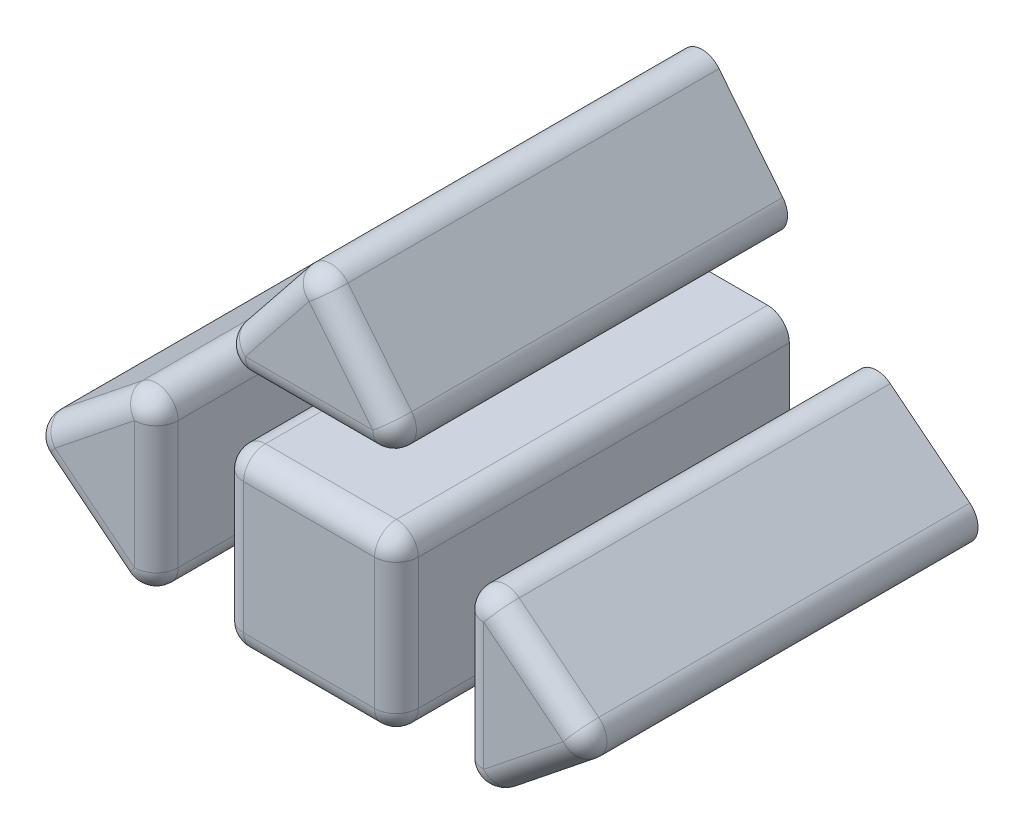
SolidWorks part; units mm, degrees
material "ABS"
ref_plane "Front Plane" through (0, 0, 0) normal (0, 0, 1) x (1, 0, 0)
ref_plane "Top Plane" through (0, 0, 0) normal (0, 1, 0) x (1, 0, 0)
ref_plane "Right Plane" through (0, 0, 0) normal (1, 0, 0) x (0, 0, -1)
sketch "Sketch1" plane through (0, 0, 0) normal (0, 0, 1) x (1, 0, 0)
  line L0 (0, -15) -> (0, 15) construction
  line L1 (-15, 0) -> (15, 0) construction
  line L2 (-0.7806, 12.27) -> (-3.699, 8.625)
  line L3 (-2.9183, 7) -> (2.9183, 7)
  line L4 (3.699, 8.625) -> (0.7806, 12.27)
  line L5 (8.625, -3.699) -> (12.27, -0.7806)
  line L6 (12.27, 0.7806) -> (8.625, 3.699)
  line L7 (7, 2.9183) -> (7, -2.9183)
  line L9 (-3, -4) -> (3, -4)
  line L10 (-4, -3) -> (-4, 3)
  line L11 (-8.625, 3.699) -> (-12.27, 0.7806)
  line L12 (-12.27, -0.7806) -> (-8.625, -3.699)
  line L13 (-7, -2.9183) -> (-7, 2.9183)
  line L14 (-3, 4) -> (3, 4)
  line L15 (4, -3) -> (4, 3)
  line L16 (-4, -4) -> (4, 4) construction
  line L20 (-4, 4) -> (4, -4) construction
  line L21 (0, -13.245) -> (5, -7) [skipped]
  line L22 (5, -7) -> (-5, -7) [skipped]
  line L23 (-5, -7) -> (0, -13.245) [skipped]
  arc A1 (-3, -4) -> (-4, -3) centre (-3, -3) cw
  arc A2 (3, -4) -> (4, -3) centre (3, -3) ccw
  arc A3 (3, 4) -> (4, 3) centre (3, 3) cw
  arc A4 (-4, 3) -> (-3, 4) centre (-3, 3) cw
  arc A5 (8.625, -3.699) -> (7, -2.9183) centre (8, -2.9183) cw
  arc A6 (12.27, -0.7806) -> (12.27, 0.7806) centre (11.645, 0) ccw
  arc A7 (8.625, 3.699) -> (7, 2.9183) centre (8, 2.9183) ccw
  arc A8 (2.9183, 7) -> (3.699, 8.625) centre (2.9183, 8) ccw
  arc A9 (-0.7806, 12.27) -> (0.7806, 12.27) centre (0, 11.645) cw
  arc A10 (-3.699, 8.625) -> (-2.9183, 7) centre (-2.9183, 8) ccw
  arc A11 (-8.625, -3.699) -> (-7, -2.9183) centre (-8, -2.9183) ccw
  arc A12 (-8.625, 3.699) -> (-7, 2.9183) centre (-8, 2.9183) cw
  arc A13 (-12.27, 0.7806) -> (-12.27, -0.7806) centre (-11.645, 0) ccw
  point P9 (0, 0)
  point P23 (0, 0)
  dimension "D6" = 1
  dimension "D7" = 1
  dimension "D1" = 7
  dimension "D5" = 8
  dimension "D4" = 4
extrude "Boss-Extrude1" add sketch "Sketch1" along normal blind 18
fillet "Fillet1" radius 1 6 edges at (0, 7, 18) (-3.8197, 7.567, 18) (-2.2398, 10.4475, 18) (0, 12.645, 18) (2.2398, 10.4475, 18) (3.8197, 7.567, 18)
fillet "Fillet2" radius 1 6 edges at (-10.4475, -2.2398, 18) (-12.645, 0, 18) (-10.4475, 2.2398, 18) (-7.567, 3.8197, 18) (-7, 0, 18) (-7.567, -3.8197, 18)
fillet "Fillet3" radius 1 8 edges at (-4, 0, 18) (-3.7071, 3.7071, 18) (0, 4, 18) (3.7071, 3.7071, 18) (4, 0, 18) (3.7071, -3.7071, 18) (0, -4, 18) (-3.7071, -3.7071, 18)
fillet "Fillet4" radius 1 6 edges at (7, 0, 18) (7.567, 3.8197, 18) (10.4475, 2.2398, 18) (12.645, 0, 18) (10.4475, -2.2398, 18) (7.567, -3.8197, 18)
